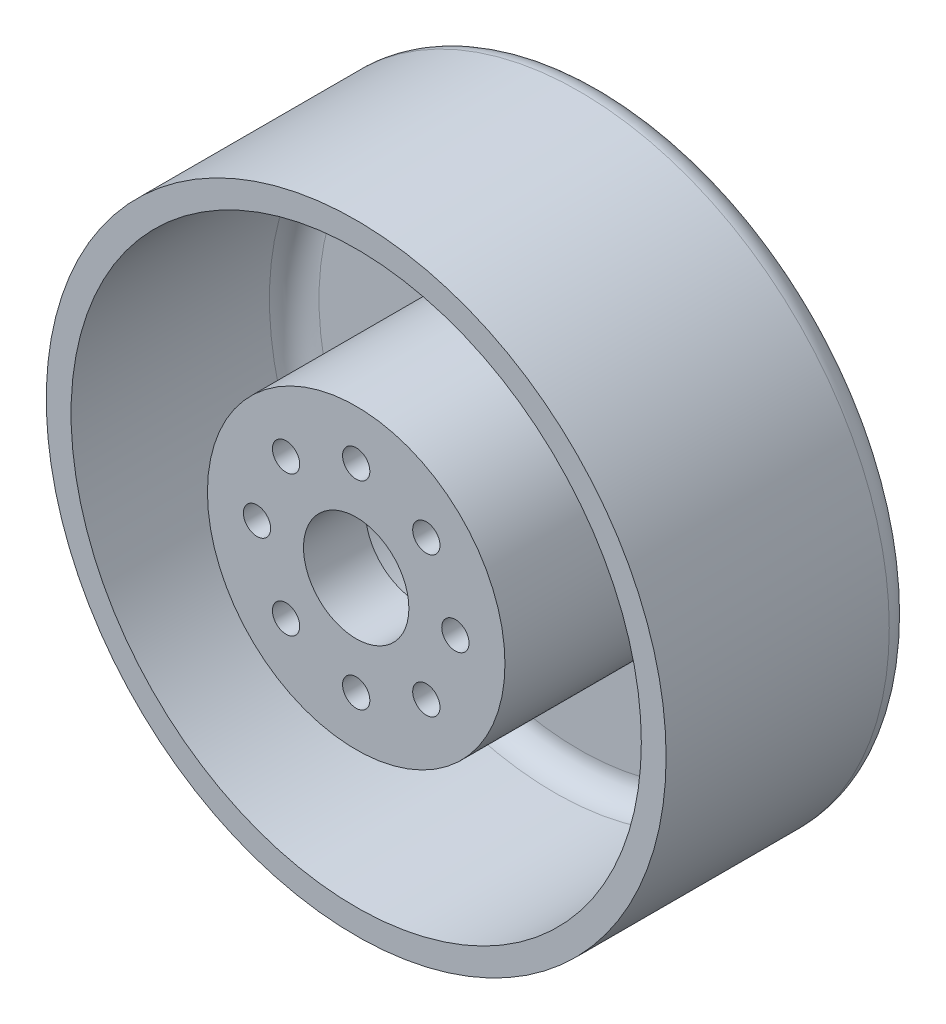
SolidWorks part; units mm, degrees
ref_plane "Front Plane" through (0, 0, 0) normal (0, 0, 1) x (1, 0, 0)
ref_plane "Top Plane" through (0, 0, 0) normal (0, 1, 0) x (1, 0, 0)
ref_plane "Right Plane" through (0, 0, 0) normal (1, 0, 0) x (0, 0, -1)
sketch "Sketch1" plane through (0, 0, 0) normal (0, 0, 1) x (1, 0, 0)
  circle A0 centre (0, 0) radius 25
  dimension "D1" = 50
extrude "Boss-Extrude1" add sketch "Sketch1" along normal blind 20
sketch "Sketch4" plane through (0, 0, 0) normal (0, 0, -1) x (-1, 0, 0)
  circle A0 centre (0, 0) radius 11
  dimension "D1" = 22
extrude "Cut-Extrude1" cut sketch "Sketch4" against normal blind 15
hole_wizard "CBORE for M2 SHCS2" positions "Sketch5" profile "Sketch6" counterbore size "M2" standard "ANSI Metric" end condition through all
sketch "Sketch5" plane through (0, 0, 15) normal (0, 0, -1) x (-1, 0, 0)
  point P0 (0, 8)
  point P7 (5.6569, 5.6569)
  point P8 (8, 0)
  point P9 (5.6569, -5.6569)
  point P10 (0, -8)
  point P11 (-5.6569, -5.6569)
  point P12 (-8, 0)
  point P13 (-5.6569, 5.6569)
  dimension "D1" = 8
  dimension "D2" = 8
sketch "Sketch6" plane through (0, 8, 15) normal (1, 0, 0) x (0, 1, 0)
  line L0 (0, 0) -> (0, 5)
  line L1 (0, 5) -> (1.1, 5)
  line L3 (1.1, 5) -> (1.1, 2)
  line L4 (1.1, 2) -> (2.2, 2)
  line L5 (2.2, 2) -> (2.2, 0)
  line L7 (2.2, 0) -> (0, 0)
  line L11 (0, -6.35) -> (0, 107.95) construction
  dimension "Thru Hole Dia." = 2.2
  dimension "Thru Hole Depth" = 5
  dimension "C'Bore Dia." = 4.4
  dimension "C'Bore Depth" = 2
sketch "Sketch7" plane through (0, 0, 20) normal (0, 0, 1) x (1, 0, 0)
  circle A0 centre (0, 0) radius 12
  circle A1 centre (0, 0) radius 23
  circle A2 centre (0, 0) radius 25 construction
  dimension "D1" = 24
  dimension "D2" = 2
extrude "Cut-Extrude2" cut sketch "Sketch7" against normal blind 18
fillet "Fillet1" radius 2 3 edges at (25, 0, 0) (23, 0, 2) (-11, 0, 0)
sketch "Sketch8" plane through (0, 0, 20) normal (0, 0, 1) x (1, 0, 0)
  circle A0 centre (0, 0) radius 4.25
  dimension "D1" = 8.5
extrude "Cut-Extrude3" cut sketch "Sketch8" against normal blind 18
